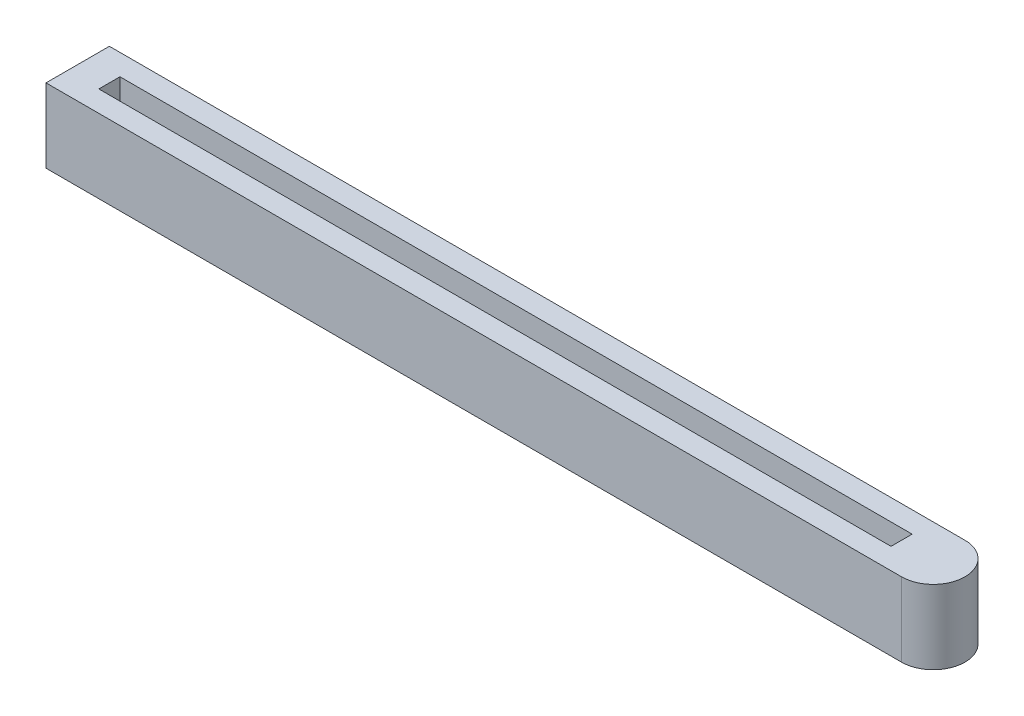
SolidWorks part; units mm, degrees
ref_plane "前视基准面" through (0, 0, 0) normal (0, 0, 1) x (1, 0, 0)
ref_plane "上视基准面" through (0, 0, 0) normal (0, 1, 0) x (1, 0, 0)
ref_plane "右视基准面" through (0, 0, 0) normal (1, 0, 0) x (0, 0, -1)
other "Configuration Table"
sketch "草图1" plane through (0, 0, 0) normal (0, 1, 0) x (1, 0, 0)
  line L6 (0, 0) -> (42, 0)
  line L7 (0, 0) -> (0, -3)
  line L8 (0, -3) -> (42, -3)
  line L9 (42, 0) -> (42, -3)
  circle A0 centre (40.5, -1.5) radius 1.5
  point P6 (1.2541, -2.7466)
  dimension "D1" = 3
  dimension "D2" = 42
extrude "凸台-拉伸1" add sketch "草图1" along normal blind 3.5 contours A0 L6 L7 L8 | A0
sketch "草图2" plane through (0, 3.5, 0) normal (0, 1, 0) x (1, 0, 0)
  line L0 (0, 0) -> (0, -3) construction
  line L1 (39, -2) -> (1.5, -2)
  line L2 (39, -2) -> (39, -1)
  line L3 (39, -1) -> (1.5, -1)
  line L4 (1.5, -2) -> (1.5, -1)
  line L5 (0, -3) -> (40.5, -3) construction
  arc A0 (40.5, -3) -> (40.5, 0) centre (40.5, -1.5) ccw construction
  point P9 (42, -1.5)
  dimension "D1" = 1
  dimension "D2" = 1.5
  dimension "D3" = 3
  dimension "D4" = 1
extrude "切除-拉伸1" cut sketch "草图2" against normal blind 1.5
